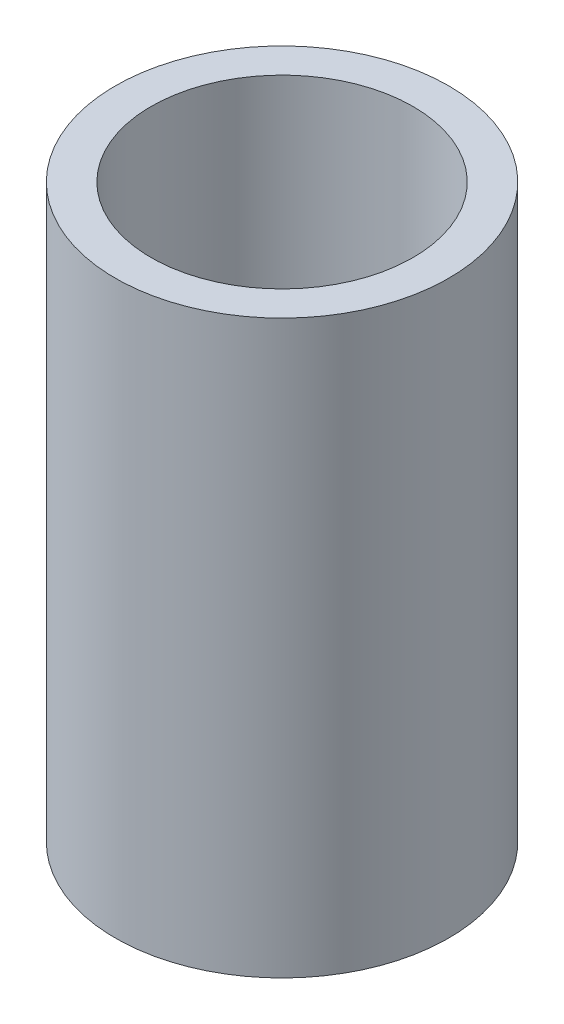
SolidWorks part; units mm, degrees
ref_plane "Front Plane" through (0, 0, 0) normal (0, 0, 1) x (1, 0, 0)
ref_plane "Top Plane" through (0, 0, 0) normal (0, 1, 0) x (1, 0, 0)
ref_plane "Right Plane" through (0, 0, 0) normal (1, 0, 0) x (0, 0, -1)
sketch "Sketch1" plane through (0, 0, 0) normal (0, 1, 0) x (1, 0, 0)
  circle A0 centre (0, 0) radius 44.45
  circle A1 centre (0, 0) radius 34.925
  dimension "D1" = 69.85
  dimension "D2" = 88.9
extrude "Boss-Extrude1" add sketch "Sketch1" along normal blind 152.4
